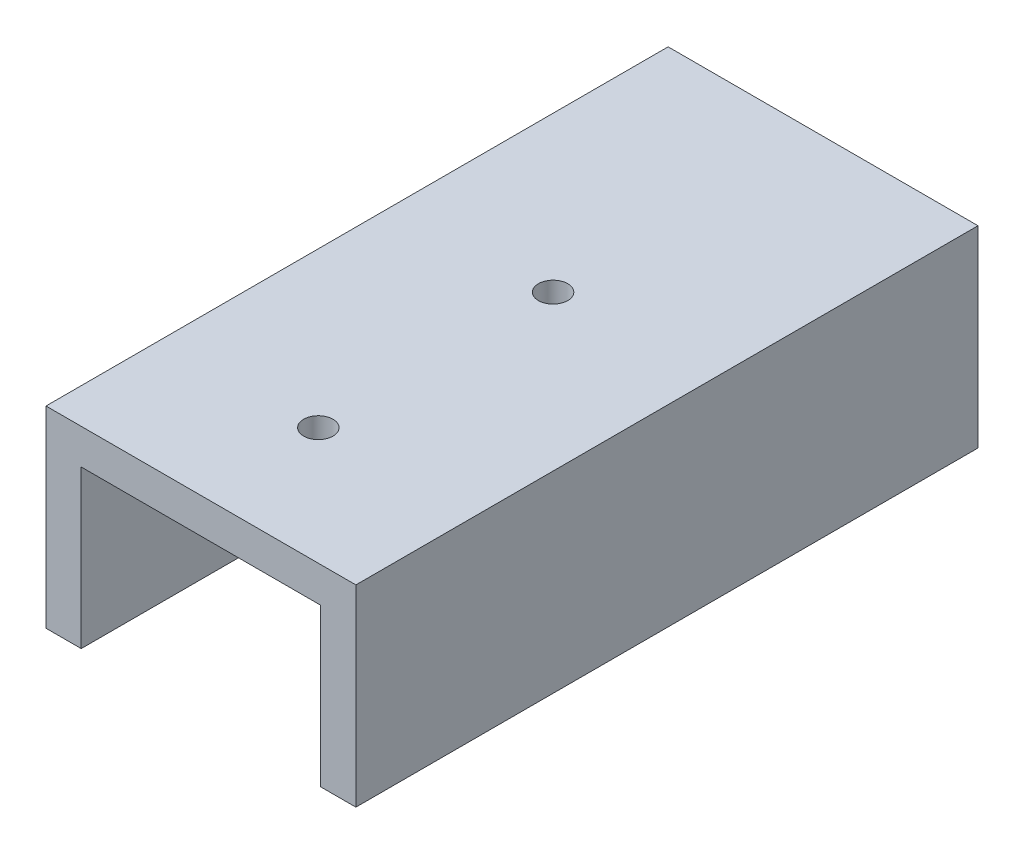
SolidWorks part; units mm, degrees
ref_plane "Front Plane" through (0, 0, 0) normal (0, 0, 1) x (1, 0, 0)
ref_plane "Top Plane" through (0, 0, 0) normal (0, 1, 0) x (1, 0, 0)
ref_plane "Right Plane" through (0, 0, 0) normal (1, 0, 0) x (0, 0, -1)
sketch "Sketch2" plane through (0, 0, 0) normal (0, 0, 1) x (1, 0, 0)
  line L1 (-10.2, 10.2) -> (10.2, 10.2)
  line L2 (-10.2, 10.2) -> (-10.2, -10.2)
  line L3 (-10.2, -10.2) -> (10.2, -10.2)
  line L4 (10.2, 10.2) -> (10.2, -10.2)
  line L5 (-10.2, 10.2) -> (10.2, -10.2) construction
  line L6 (-10.2, -10.2) -> (10.2, 10.2) construction
  line L7 (-13.2, 13.2) -> (13.2, 13.2)
  line L8 (-13.2, 13.2) -> (-13.2, -13.2)
  line L9 (-13.2, -13.2) -> (13.2, -13.2)
  line L10 (13.2, 13.2) -> (13.2, -13.2)
  line L11 (-13.2, 13.2) -> (13.2, -13.2) construction
  line L12 (-13.2, -13.2) -> (13.2, 13.2) construction
  point P0 (0, 0)
  point P6 (0, 0)
  dimension "D1" = 20.4
  dimension "D2" = 20.4
  dimension "D3" = 26.4
  dimension "D4" = 26.4
extrude "Boss-Extrude1" add sketch "Sketch2" along normal blind 50
sketch "Sketch3" plane through (0, 0, 0) normal (0, 0, -1) x (-1, 0, 0)
  line L0 (13.2, 13.2) -> (13.2, -13.2) construction
  line L1 (13.2, -13.2) -> (-13.2, -13.2) construction
  line L2 (-13.2, -13.2) -> (-13.2, 13.2) construction
  line L3 (-13.2, 13.2) -> (13.2, 13.2) construction
  line L4 (13.2, 13.2) -> (13.2, -13.2)
  line L5 (13.2, -13.2) -> (-13.2, -13.2)
  line L6 (-13.2, -13.2) -> (-13.2, 13.2)
  line L7 (-13.2, 13.2) -> (13.2, 13.2)
extrude "Boss-Extrude2" add sketch "Sketch3" along normal blind 3
sketch "Sketch4" plane through (0, -13.2, 0) normal (0, -1, 0) x (1, 0, 0)
  line L4 (-10.2, 0) -> (10.2, 0)
  line L5 (-10.2, 50) -> (-10.2, 0)
  line L6 (10.2, 50) -> (-10.2, 50)
  line L7 (10.2, 0) -> (10.2, 50)
  line L8 (-10.2, 0) -> (10.2, 0)
  line L9 (-10.2, 50) -> (-10.2, 0)
  line L10 (10.2, 50) -> (-10.2, 50)
  line L11 (10.2, 0) -> (10.2, 50)
  dimension "D1" = 0
extrude "Cut-Extrude1" cut sketch "Sketch4" against normal blind 3
sketch "Sketch5" plane through (0, -13.2, 0) normal (0, -1, 0) x (1, 0, 0)
  line L1 (-13.2, 50) -> (13.2, 50)
  line L2 (-13.2, 50) -> (-13.2, -3)
  line L3 (-13.2, -3) -> (13.2, -3)
  line L4 (13.2, 50) -> (13.2, -3)
extrude "Cut-Extrude2" cut sketch "Sketch5" against normal blind 10
sketch "Sketch6" plane through (0, 13.2, 0) normal (0, 1, 0) x (1, 0, 0)
  line L1 (13.2, -50) -> (13.2, 3) construction
  line L2 (-13.2, -50) -> (-13.2, 3) construction
  line L3 (10.2, 0) -> (-10.2, 0) construction
  circle A0 centre (0, -20) radius 1.25
  circle A1 centre (0, -40) radius 1.25
  dimension "D3" = 2.5
  dimension "D4" = 2.5
  dimension "D1" = 20
  dimension "D2" = 40
  dimension "D5" = 13.2
  dimension "D6" = 13.2
extrude "Cut-Extrude3" cut sketch "Sketch6" against normal blind 10
sketch "Sketch7" plane through (0, 13.2, 0) normal (0, 1, 0) x (1, 0, 0)
  line L0 (-13.2, 3) -> (13.2, 3) construction
  text T0 "<b>H</b>"
  point P4 (0, 3)
extrude "Cut-Extrude4" [suppressed] cut sketch "Sketch7" against normal blind 10
